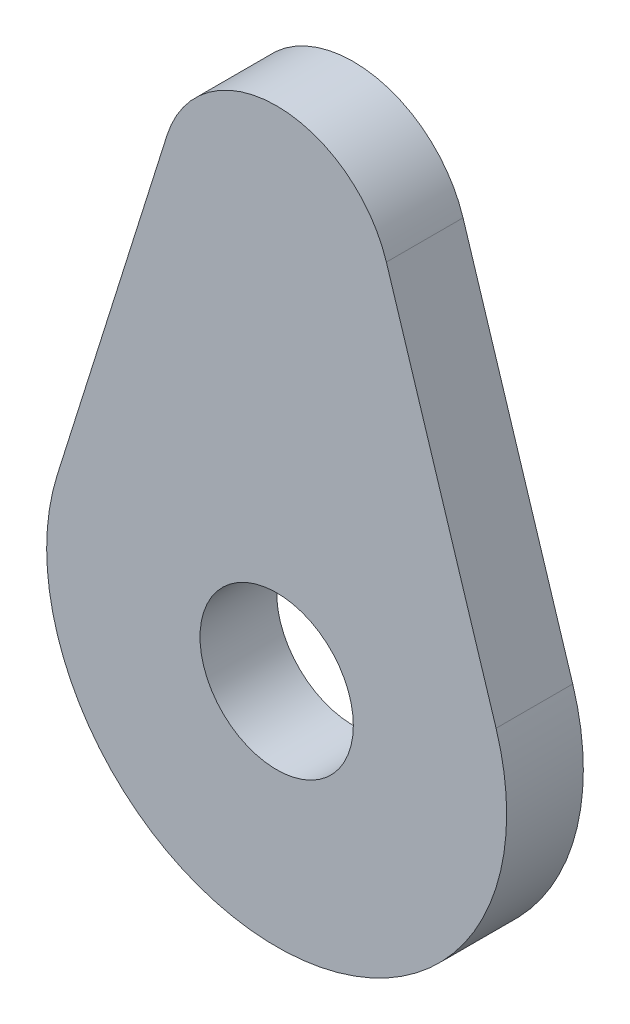
SolidWorks part; units mm, degrees
ref_plane "Front Plane" through (0, 0, 0) normal (0, 0, 1) x (1, 0, 0)
ref_plane "Top Plane" through (0, 0, 0) normal (0, 1, 0) x (1, 0, 0)
ref_plane "Right Plane" through (0, 0, 0) normal (1, 0, 0) x (0, 0, -1)
sketch "Sketch1" plane through (0, 0, 0) normal (0, 0, 1) x (1, 0, 0)
  line L0 (-14.3091, 54.5) -> (-28.6182, 9)
  line L1 (0, 86.1378) -> (0, -50.6287) construction
  line L2 (14.3091, 54.5) -> (28.6182, 9)
  arc A0 (-28.6182, 9) -> (28.6182, 9) centre (0, 0) ccw
  arc A1 (14.3091, 54.5) -> (-14.3091, 54.5) centre (0, 50) ccw
  circle A2 centre (0, 0) radius 10
  dimension "D1" = 60
  dimension "D2" = 30
  dimension "D4" = 20
  dimension "D3" = 50
extrude "Boss-Extrude1" add sketch "Sketch1" along normal mid plane 10 contours L0 A0 L2 A1 | A2
